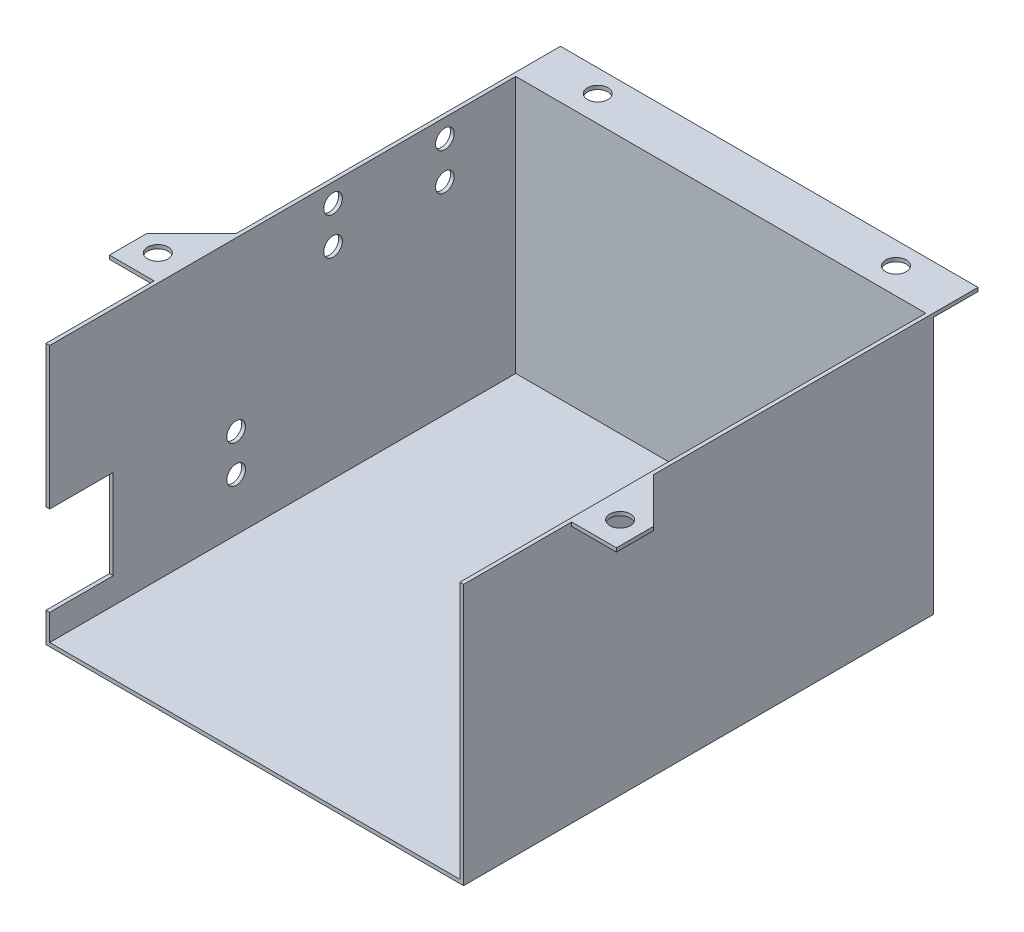
SolidWorks part; units mm, degrees
material "普通碳钢"
ref_plane "前视基准面" through (0, 0, 0) normal (0, 0, 1) x (1, 0, 0)
ref_plane "上视基准面" through (0, 0, 0) normal (0, 1, 0) x (1, 0, 0)
ref_plane "右视基准面" through (0, 0, 0) normal (1, 0, 0) x (0, 0, -1)
sketch "草图1" plane through (0, 0, 0) normal (0, 0, 1) x (1, 0, 0)
  line L1 (0, 0) -> (112, 0)
  line L2 (0, 0) -> (0, 70)
  line L3 (0, 70) -> (112, 70)
  line L4 (112, 0) -> (112, 70)
  dimension "D1" = 112
  dimension "D2" = 70
extrude "拉伸1" add sketch "草图1" along normal blind 126
sketch "草图2" plane through (0, 0, 126) normal (0, 0, 1) x (1, 0, 0)
  line L0 (112, 70) -> (0, 70) construction
  line L1 (1, 70) -> (111, 70)
  line L2 (1, 70) -> (1, 1)
  line L3 (1, 1) -> (111, 1)
  line L4 (111, 70) -> (111, 1)
  line L5 (56, 0) -> (56, 95.8149) construction
  line L6 (0, 0) -> (112, 0) construction
  dimension "D1" = 110
  dimension "D2" = 1
extrude "切除-拉伸1" cut sketch "草图2" against normal blind 125
sketch "草图3" plane through (0, 0, 0) normal (0, 0, -1) x (-1, 0, 0)
  line L0 (0, 70) -> (0, 0) construction
  line L1 (-112, 70) -> (0, 70)
  line L2 (-112, 70) -> (-112, 69)
  line L3 (-112, 69) -> (0, 69)
  line L4 (0, 70) -> (0, 69)
  dimension "D1" = 1
extrude "拉伸2" add sketch "草图3" along normal blind 12
sketch "草图4" plane through (112, 0, 0) normal (1, 0, 0) x (0, 0, -1)
  line L0 (-126, 70) -> (12, 70) construction
  line L1 (-97, 70) -> (-75, 70)
  line L2 (-97, 70) -> (-97, 69)
  line L3 (-97, 69) -> (-75, 69)
  line L4 (-75, 70) -> (-75, 69)
  line L5 (0, 0) -> (0, 69) construction
  dimension "D1" = 75
  dimension "D2" = 1
  dimension "D3" = 22
extrude "拉伸3" add sketch "草图4" along normal blind 12
sketch "草图5" plane through (0, 70, 0) normal (0, 1, 0) x (-1, 0, 0)
  line L0 (-112, 75) -> (-124, 87)
  line L1 (-124, 75) -> (-124, 97) construction
  line L2 (-124, 87) -> (-124, 75)
  line L3 (-124, 75) -> (-112, 75)
  dimension "D1" = 45
extrude "切除-拉伸2" cut sketch "草图5" against normal blind 10
ref_plane "基准面1" through (56, 0, 0) normal (-1, 0, 0) x (0, 0, 1)
mirror "镜向1" about plane through (56, 0, 0) normal (-1, 0, 0) of "拉伸3"
mirror "镜向2" about plane through (56, 0, 0) normal (-1, 0, 0) of "切除-拉伸2"
sketch "草图6" plane through (0, 69, 0) normal (0, -1, 0) x (1, 0, 0)
  line L0 (56, -12) -> (56, 79.8479) construction
  line L1 (112, -12) -> (0, -12) construction
  line L2 (56, 29.4217) -> (56, -29.4217) construction
  line L3 (0, 97) -> (0, 75) construction
  line L4 (-12, 97) -> (0, 97) construction
  circle A0 centre (-6, 90) radius 2.75
  circle A1 centre (118, 90) radius 2.75
  circle A2 centre (16, -6) radius 2.75
  circle A3 centre (96, -6) radius 2.75
  dimension "D1" = 5.5
  dimension "D2" = 6
  dimension "D3" = 40
  dimension "D4" = 7
  dimension "D5" = 6
extrude "切除-拉伸3" cut sketch "草图6" against normal through all
sketch "草图7" plane through (112, 0, 0) normal (1, 0, 0) x (0, 0, -1)
  line L0 (-126, 0) -> (-126, 70) construction
  line L1 (-126, 32) -> (-109, 32)
  line L2 (-126, 32) -> (-126, 8)
  line L3 (-126, 8) -> (-109, 8)
  line L4 (-109, 32) -> (-109, 8)
  line L5 (-126, 0) -> (0, 0) construction
  dimension "D1" = 8
  dimension "D2" = 17
  dimension "D3" = 24
sketch "草图8" plane through (0, 0, 0) normal (-1, 0, 0) x (0, 0, 1)
  line L1 (126, 32) -> (109, 32)
  line L2 (126, 32) -> (126, 8)
  line L3 (126, 8) -> (109, 8)
  line L4 (109, 32) -> (109, 8)
extrude "切除-拉伸5" cut sketch "草图8" against normal up to next
sketch "草图9" plane through (0, 0, 0) normal (-1, 0, 0) x (0, 0, 1)
  line L0 (20, 65) -> (50, 65) construction
  line L1 (50, 55) -> (20, 55) construction
  line L2 (126, 0) -> (0, 0) construction
  line L3 (0, 69) -> (0, 0) construction
  line L4 (20, 65) -> (20, 55) construction
  line L5 (50, 65) -> (50, 55) construction
  line L6 (76, 25) -> (76, 15) construction
  line L7 (126, 32) -> (126, 8) construction
  circle A0 centre (20, 65) radius 2.5
  circle A1 centre (20, 55) radius 2.5
  circle A2 centre (50, 65) radius 2.5
  circle A3 centre (50, 55) radius 2.5
  circle A4 centre (76, 25) radius 2.5
  circle A5 centre (76, 15) radius 2.5
  dimension "D1" = 5
  dimension "D6" = 50
  dimension "D2" = 10
  dimension "D3" = 55
  dimension "D4" = 20
  dimension "D5" = 30
  dimension "D7" = 10
  dimension "D8" = 15
extrude "切除-拉伸6" cut sketch "草图9" against normal blind 10
